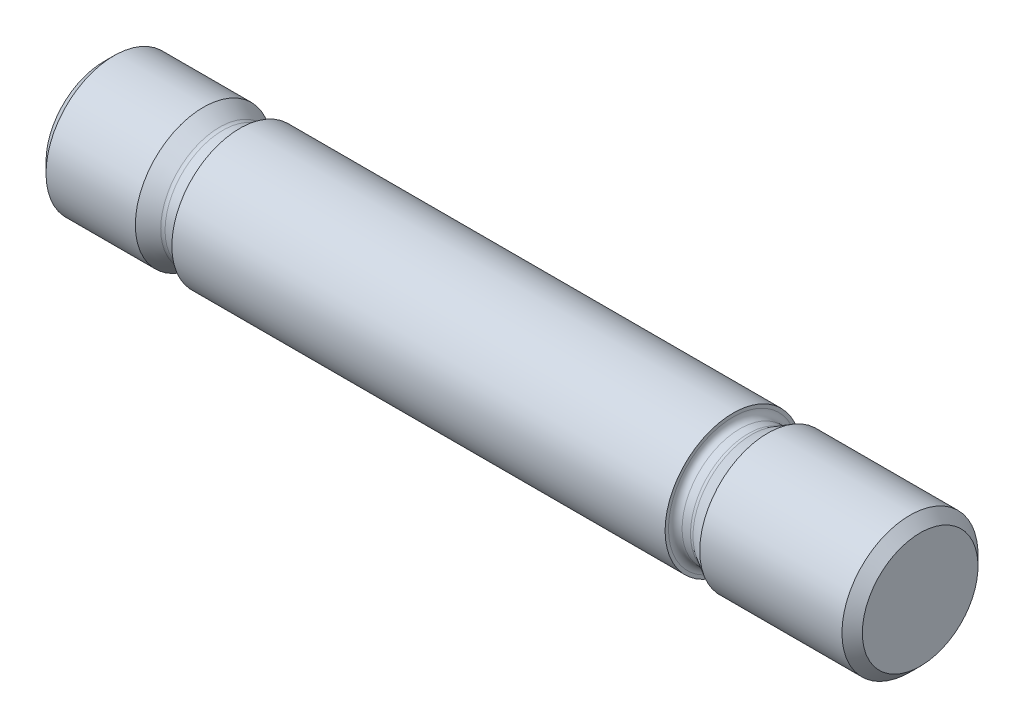
SolidWorks part; units mm, degrees
revolve "BaseBody" add sketch "BodySke" angle 360 about L14
sketch "BodySke" plane through (0, 0, 0) normal (0, 0, 1) x (1, 0, 0)
  line L0 (17, 8.634) -> (14.634, 10)
  line L1 (14.634, 10) -> (1.5, 10)
  line L2 (20, 10) -> (20, 9.5)
  line L3 (19, 8.5) -> (17.5, 8.5)
  line L5 (1.5, 10) -> (0, 8.5)
  line L7 (92.5019, 10) -> (92.5019, 9.5)
  line L8 (93.5019, 8.5) -> (94.734, 8.5)
  line L9 (95.234, 8.634) -> (97.6, 10)
  line L10 (97.6, 10) -> (118.5, 10)
  line L11 (118.5, 10) -> (120, 8.5)
  line L12 (120, 8.5) -> (120, 0)
  line L13 (120, 0) -> (0, 0)
  line L14 (-3.175, 0) -> (101.6, 0) construction
  line L15 (99.7895, -8.5) -> (120, -8.5) construction
  line L16 (92.5019, -8.5) -> (95.0019, -8.5) construction
  line L17 (11.034, -10) -> (92.5019, -10) construction
  line L18 (0, 8.5) -> (0, 0)
  line L19 (20, 10) -> (92.5019, 10)
  line L20 (97.0019, 13.3514) -> (97.0019, -4.0014) construction
  line L21 (97.6, 12.2761) -> (97.6, -3.5735) construction
  arc A0 (17.5, 8.5) -> (17, 8.634) centre (17.5, 9.5) cw
  arc A1 (20, 9.5) -> (19, 8.5) centre (19, 9.5) cw
  arc A2 (94.734, 8.5) -> (95.234, 8.634) centre (94.734, 9.5) ccw
  arc A3 (92.5019, 9.5) -> (93.5019, 8.5) centre (93.5019, 9.5) ccw
  point P26 (95.0019, 8.5)
  point P29 (92.5019, 8.5)
  dimension "Thread_neck_width" = 2.5
  dimension "Thread_nom" = 22.4
  dimension "Advance" = 2
  dimension "Thread_lim" = 22.9981
  dimension "Shoulder_neck_width" = 2.5
  dimension "Studend_length" = 20
  dimension "Length" = 100
  dimension "Thread_len" = 22.4
cosmetic thread "ThreadCosmetic" [suppressed] parameters "Thread_minor"=17
cosmetic thread "ThreadCosmeticStud" [suppressed] parameters "Thrd_minor"=17
ref_plane "Plane1" through (0, 0, 0) normal (0, 0, 1) x (1, 0, 0)
ref_plane "Plane2" through (0, 0, 0) normal (0, 1, 0) x (1, 0, 0)
ref_plane "Plane3" through (0, 0, 0) normal (1, 0, 0) x (0, 0, -1)
sketch "ThdSchSke" plane through (0, 0, 0) normal (0, 0, 1) x (1, 0, 0)
  line L0 (97.6, -8.5) -> (96.5497, -10)
  line L1 (97.6, -8.5) -> (98.6503, -10)
  line L2 (98.6503, -10) -> (98.6503, -12.5)
  line L3 (-3.175, 0) -> (5.1513, 0) construction
  line L4 (120, -8.5) -> (120, 8.5) construction
  line L5 (98.6503, -12.5) -> (96.5497, -12.5)
  line L6 (96.5497, -12.5) -> (96.5497, -10)
  dimension "Thread_minor" = 17
  dimension "Diameter" = 20
  dimension "Start" = 22.4
  dimension "SideAngle" = 55
  dimension "VeeAngle" = 70
  dimension "Overcut" = 25
revolve "ThreadSchematic" [suppressed] cut sketch "ThdSchSke" angle 360 about L3
pattern_linear "ThdSchPat" [suppressed]
sketch "ThdSchSketStud" plane through (0, 0, 0) normal (0, 0, 1) x (1, 0, 0)
  line L0 (15.5, -8.5) -> (14.4497, -10)
  line L1 (15.5, -8.5) -> (16.5503, -10)
  line L2 (16.5503, -10) -> (16.5503, -12.5)
  line L3 (-3.175, 0) -> (5.1513, 0) construction
  line L5 (16.5503, -12.5) -> (14.4497, -12.5)
  line L6 (14.4497, -12.5) -> (14.4497, -10)
  line L7 (0, 8.5) -> (0, -8.5) construction
  dimension "Thread_minor" = 17
  dimension "Diameter" = 20
  dimension "SideAngle" = 55
  dimension "VeeAngle" = 70
  dimension "Overcut" = 25
revolve "ThreadSchematicStud" [suppressed] cut sketch "ThdSchSketStud" angle 360 about L3
pattern_linear "ThdSchPatStud" [suppressed]
equation "\"Thread_minor@ThreadCosmetic\" = \"Minor_dia@BodySke\""
equation "\"Thrd_minor@ThreadCosmeticStud\" = \"Thread_minor@ThreadCosmetic\""
equation "\"Thread_len@BodySke\" = \"Thread_nom@BodySke\""
equation "\"Thread_minor@ThdSchSke\" = \"Minor_dia@BodySke\""
equation "\"Diameter@ThdSchSke\" = \"Thread_dia@BodySke\""
equation "\"Overcut@ThdSchSke\" = \"Thread_dia@BodySke\" * 1.25"
equation "\"Start@ThdSchSke\" = \"Thread_nom@BodySke\"  '   - \"Advance@BodySke\""
equation "\"Num_threads@ThdSchPat\" = int( \"Thread_len@BodySke\" / \"Advance@BodySke\" + 0.999 ) + 1"
equation "\"Advance@ThdSchPat\" = \"Thread_nom@BodySke\" /  ( \"Num_threads@ThdSchPat\" - 1 ) 'relax it"
equation "\"Num_threads@ThdSchPat\" = \"Num_threads@ThdSchPat\" - sgn( \"Num_threads@ThdSchPat\" - 1 ) '---chamfered tips only---"
equation "\"Diameter@ThdSchSketStud\" = \"Diameter@ThdSchSke\""
equation "\"Thread_minor@ThdSchSketStud\" = \"Thread_minor@ThdSchSke\""
equation "\"Overcut@ThdSchSketStud\" = \"Overcut@ThdSchSke\""
equation "\"Start_@ThdSchSketStud\" = \"Studend_length@BodySke\" - \"Shoulder_neck_width@BodySke\" - \"Advance@BodySke\""
equation "\"Num_threads@ThdSchPatStud\" = int( \"Start_@ThdSchSketStud\"/ \"Advance@BodySke\" + 0.999 )  + 1"
equation "\"Advance@ThdSchPatStud\" = \"Start_@ThdSchSketStud\" /  ( \"Num_threads@ThdSchPatStud\" - 1 ) 'relax it"
